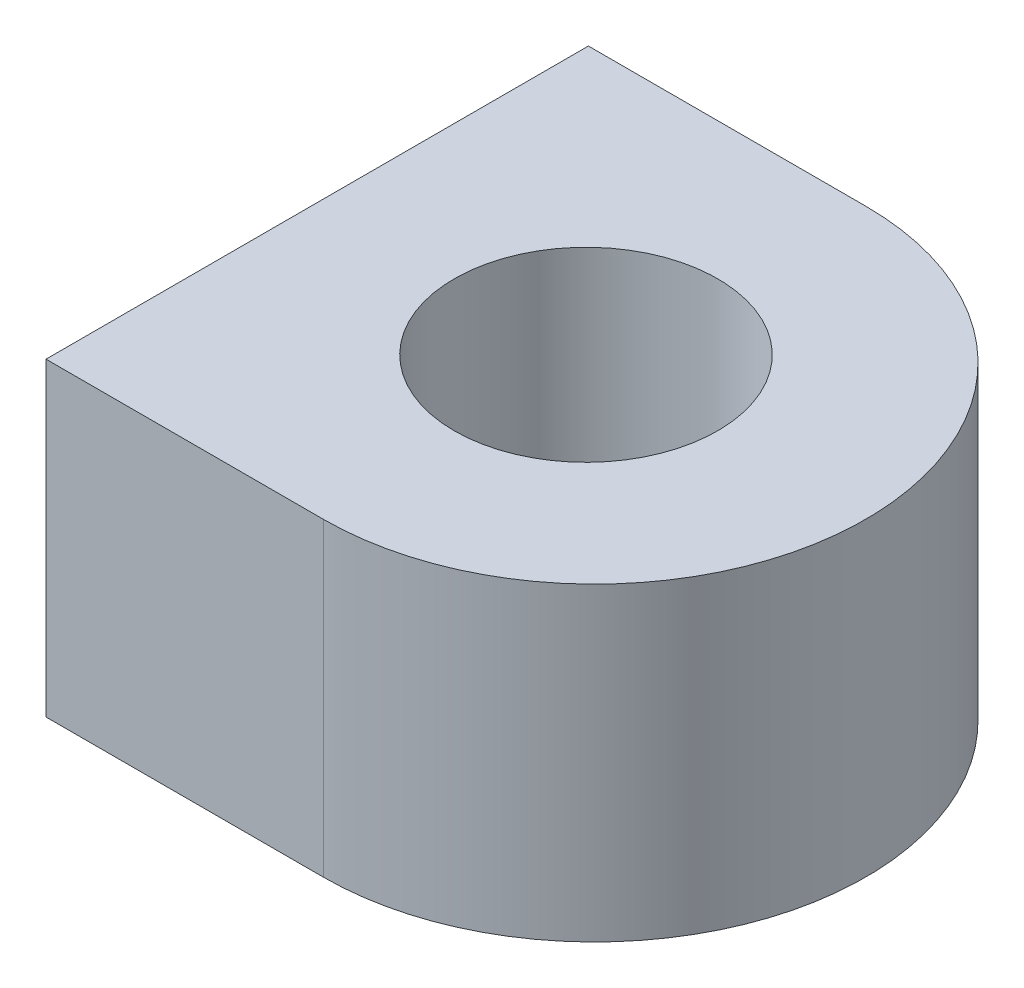
SolidWorks part; units mm, degrees
ref_plane "Front Plane" through (0, 0, 0) normal (0, 0, 1) x (1, 0, 0)
ref_plane "Top Plane" through (0, 0, 0) normal (0, 1, 0) x (1, 0, 0)
ref_plane "Right Plane" through (0, 0, 0) normal (1, 0, 0) x (0, 0, -1)
sketch "Sketch1" plane through (0, 0, 0) normal (0, 1, 0) x (1, 0, 0)
  line L0 (-3.4358, -0.0334) -> (-3.4358, 3.4666)
  line L1 (-3.4358, -0.0334) -> (-3.4358, -3.5334)
  line L5 (-3.4358, -3.5334) -> (0.1437, -3.5334)
  line L6 (-3.4358, 3.4666) -> (0.1437, 3.4666)
  circle A2 centre (0, 0) radius 1.7
  arc A4 (0.1437, 3.4666) -> (0.1437, -3.5334) centre (0.1437, -0.0334) cw
  dimension "D1" = 3.4
  dimension "D2" = 3.5
extrude "Boss-Extrude2" add sketch "Sketch1" along normal blind 4
